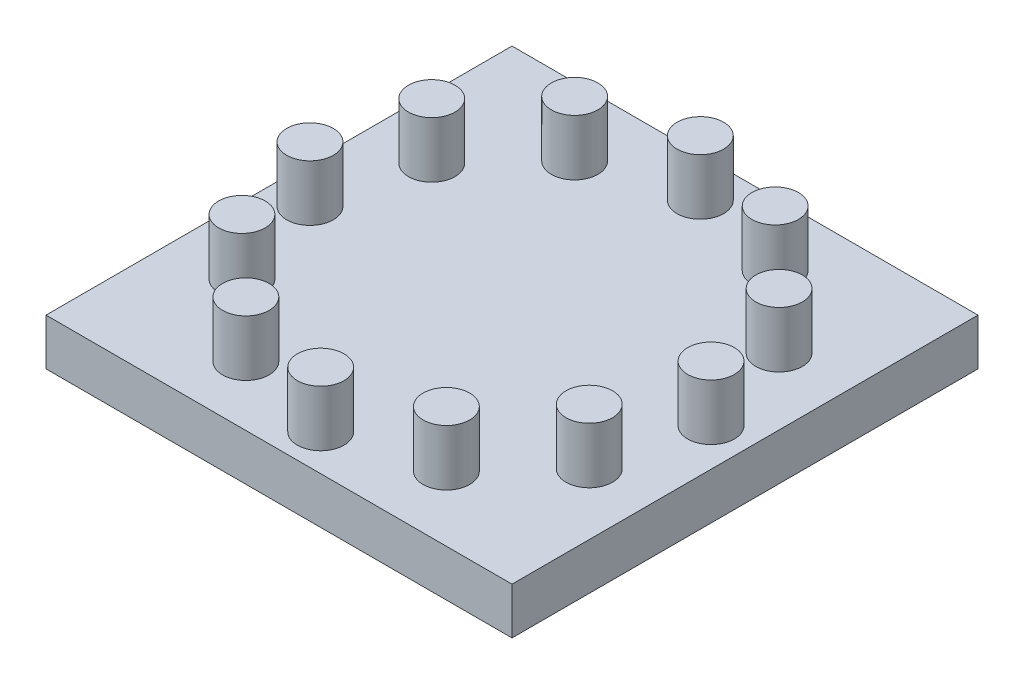
SolidWorks part; units mm, degrees
ref_plane "Alzado" through (0, 0, 0) normal (0, 0, 1) x (1, 0, 0)
ref_plane "Planta" through (0, 0, 0) normal (0, 1, 0) x (1, 0, 0)
ref_plane "Vista lateral" through (0, 0, 0) normal (1, 0, 0) x (0, 0, -1)
sketch "Croquis1" plane through (0, 0, 0) normal (0, 1, 0) x (1, 0, 0)
  line L1 (-50, 50) -> (50, 50)
  line L2 (-50, 50) -> (-50, -50)
  line L3 (-50, -50) -> (50, -50)
  line L4 (50, 50) -> (50, -50)
  line L5 (-50, 50) -> (50, -50) construction
  line L6 (-50, -50) -> (50, 50) construction
  point P0 (0, 0)
  dimension "D1" = 100
  dimension "D2" = 100
extrude "Saliente-Extruir1" add sketch "Croquis1" along normal blind 10
sketch "Croquis2" plane through (0, 10, 0) normal (0, 1, 0) x (1, 0, 0)
  circle A0 centre (-1.1404, 41.5535) radius 5
  dimension "D1" = 10
extrude "Saliente-Extruir2" add sketch "Croquis2" along normal blind 12
pattern_circular "MatrizC1" count 12 over 360 about axis through (0.009, 0, 0.3289) along (0, 1, 0) of "Saliente-Extruir2"
